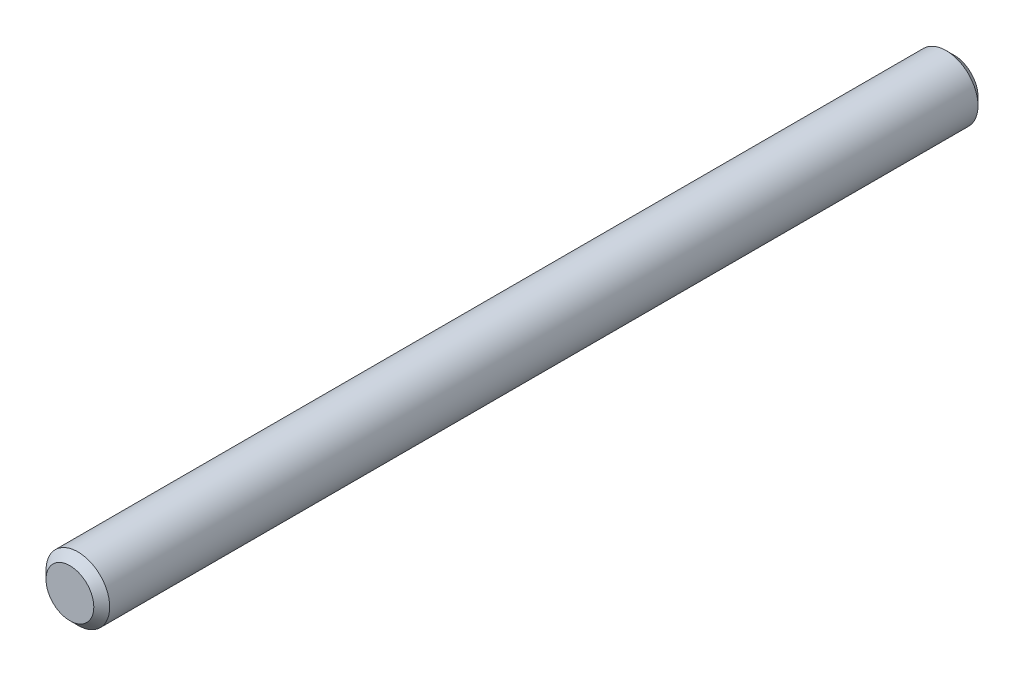
SolidWorks part; units mm, degrees
ref_plane "Front Plane" through (0, 0, 0) normal (0, 0, 1) x (1, 0, 0)
ref_plane "Top Plane" through (0, 0, 0) normal (0, 1, 0) x (1, 0, 0)
ref_plane "Right Plane" through (0, 0, 0) normal (1, 0, 0) x (0, 0, -1)
sketch "Sketch1" plane through (0, 0, 0) normal (0, 0, 1) x (1, 0, 0)
  circle A0 centre (0, 0) radius 4
  dimension "D1" = 8
extrude "Boss.-Extru.1" add sketch "Sketch1" along normal blind 111 contours A0
chamfer "Chanfrein1" distance 1 angle 45 2 edges at (4, 0, 0) (4, 0, 111)
